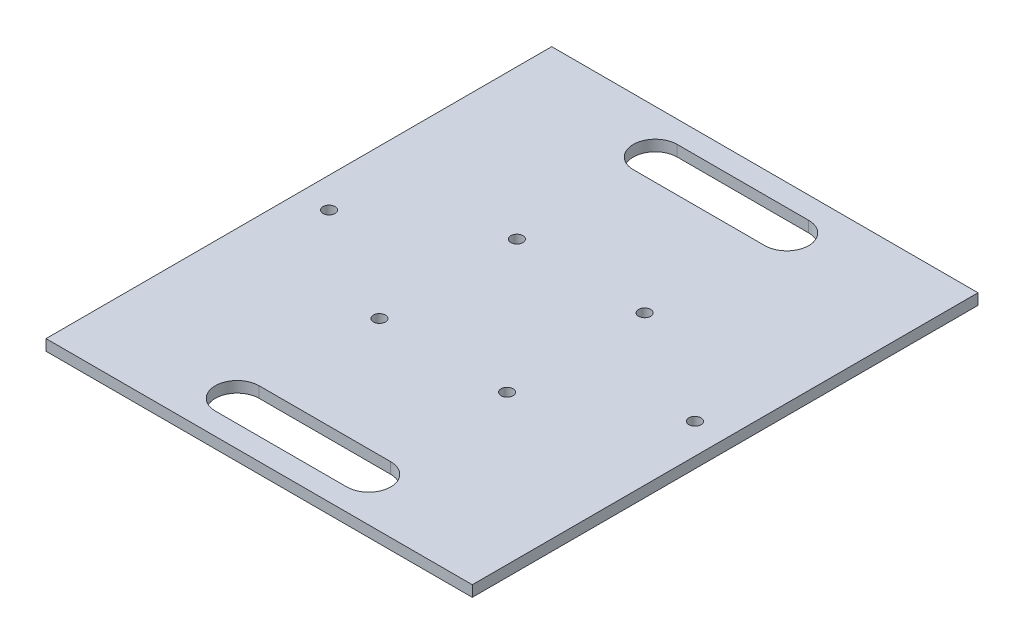
SolidWorks part; units mm, degrees
material "Acrylic (Medium-high impact)"
ref_plane "Front Plane" through (0, 0, 0) normal (0, 0, 1) x (1, 0, 0)
ref_plane "Top Plane" through (0, 0, 0) normal (0, 1, 0) x (1, 0, 0)
ref_plane "Right Plane" through (0, 0, 0) normal (1, 0, 0) x (0, 0, -1)
sketch "Sketch1" plane through (0, 0, 0) normal (0, 1, 0) x (1, 0, 0)
  line L1 (-123.5, -146.5) -> (123.5, -146.5)
  line L2 (-123.5, -146.5) -> (-123.5, 146.5)
  line L3 (-123.5, 146.5) -> (123.5, 146.5)
  line L4 (123.5, -146.5) -> (123.5, 146.5)
  line L5 (-123.5, -146.5) -> (123.5, 146.5) construction
  line L6 (-123.5, 146.5) -> (123.5, -146.5) construction
  point P0 (0, 0)
  dimension "D1" = 293
  dimension "D2" = 247
extrude "Main Base" add sketch "Sketch1" along normal mid plane 6.35
sketch "Sketch2" plane through (0, 3.175, 0) normal (0, 1, 0) x (1, 0, 0)
  line L0 (-38.1, 121.1) -> (38.1, 121.1) construction
  line L1 (-38.1, 133.8) -> (38.1, 133.8)
  line L2 (-38.1, 108.4) -> (38.1, 108.4)
  line L3 (123.5, 146.5) -> (-123.5, 146.5) construction
  line L4 (-1000, 0) -> (49000, 0) construction
  line L5 (-38.1, -121.1) -> (38.1, -121.1) construction
  line L6 (-38.1, -133.8) -> (38.1, -133.8)
  line L7 (-38.1, -108.4) -> (38.1, -108.4)
  arc A0 (-38.1, 133.8) -> (-38.1, 108.4) centre (-38.1, 121.1) ccw
  arc A1 (38.1, 108.4) -> (38.1, 133.8) centre (38.1, 121.1) ccw
  arc A2 (-38.1, -133.8) -> (-38.1, -108.4) centre (-38.1, -121.1) cw
  arc A3 (38.1, -108.4) -> (38.1, -133.8) centre (38.1, -121.1) cw
  point P2 (0, 121.1)
  point P14 (0, -121.1)
  dimension "D2" = 25.4
  dimension "D1" = 25.4
  dimension "D3" = 76.2
extrude "Handles" cut sketch "Sketch2" against normal through all
sketch "Sketch4" plane through (0, 3.175, 0) normal (0, 1, 0) x (1, 0, 0)
  line L0 (0, -3.4925) -> (0, 3.4925) construction
  circle A0 centre (-60, 0) radius 49 construction
  circle A1 centre (-106, 0) radius 3 construction
  circle A2 centre (-37, 39.8372) radius 3 construction
  circle A3 centre (-37, -39.8372) radius 3 construction
  circle A7 centre (37, -39.8372) radius 3 construction
  circle A8 centre (37, 39.8372) radius 3 construction
  circle A9 centre (106, 0) radius 3 construction
  circle A10 centre (60, 0) radius 49 construction
  point P7 (-60, 0)
  point P13 (-60, 0)
  point P23 (60, 0)
  point P24 (60, 0)
  dimension "D1" = 98
  dimension "D3" = 6
  dimension "D2" = 60
  dimension "D4" = 3
sketch "Sketch5" plane through (0, 3.175, 0) normal (0, 1, 0) x (1, 0, 0)
  point P0 (-106, 0)
  point P3 (-37, -39.8372)
  point P6 (-37, 39.8372)
  point P10 (37, 39.8372)
  point P13 (37, -39.8372)
  point P16 (106, 0)
hole_wizard "Alignment Holes" positions "Sketch5" profile "Sketch6" hole size "#97" standard "ANSI Inch" end condition through all
sketch "Sketch6" plane through (-106, 3.175, 0) normal (1, 0, 0) x (0, 0, 1)
  line L0 (0, 0) -> (0, 6.35)
  line L1 (0, 6.35) -> (3.5, 6.35)
  line L2 (3.5, 6.35) -> (3.5, 0)
  line L5 (3.5, 0) -> (0, 0)
  line L11 (0, -6.35) -> (0, 107.95) construction
  dimension "Thru Hole Dia." = 7
  dimension "Thru Hole Depth" = 6.35
